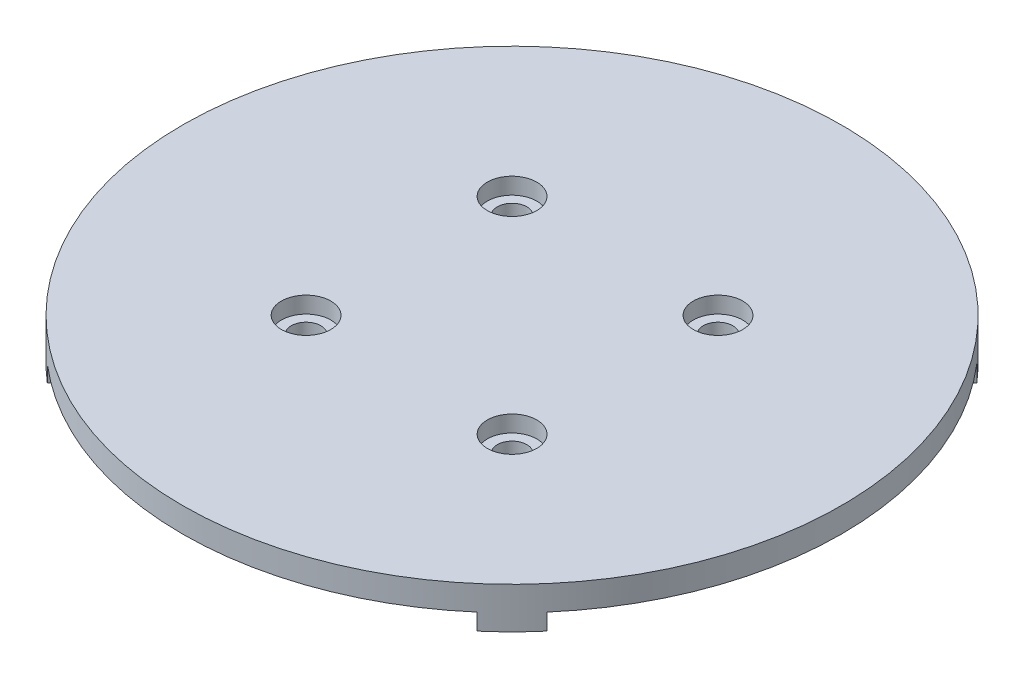
SolidWorks part; units mm, degrees
ref_plane "前视基准面" through (0, 0, 0) normal (0, 0, 1) x (1, 0, 0)
ref_plane "上视基准面" through (0, 0, 0) normal (0, 1, 0) x (1, 0, 0)
ref_plane "右视基准面" through (0, 0, 0) normal (1, 0, 0) x (0, 0, -1)
sketch "草图1" plane through (0, 0, 0) normal (0, 1, 0) x (1, 0, 0)
  circle A0 centre (0, 0) radius 40
  dimension "D1" = 80
extrude "凸台-拉伸1" add sketch "草图1" along normal blind 3 contours A0
sketch "草图2" plane through (0, 0, 0) normal (0, -1, 0) x (1, 0, 0)
  line L0 (-71.7271, 0) -> (80.6754, 0) construction
  line L1 (0, -61.079) -> (0, 71.7562) construction
  circle A0 centre (0, 0) radius 35
  circle A1 centre (0, 0) radius 30
extrude "凸台-拉伸2" add sketch "草图2" along normal blind 2
sketch "草图3" plane through (0, 0, 0) normal (0, -1, 0) x (1, 0, 0)
  circle A0 centre (0, 0) radius 15
  circle A1 centre (0, 0) radius 20
extrude "凸台-拉伸3" add sketch "草图3" along normal blind 5
sketch "草图5" plane through (0, 0, 0) normal (0, -1, 0) x (-1, 0, 0)
  line L0 (46.2077, -12.5) -> (-62.2408, -12.5) construction
  line L1 (12.5, -50.4142) -> (12.5, 52.4511) construction
  line L2 (-12.5, -45.8753) -> (-12.5, 58.6819)
  line L3 (-66.8088, 12.5) -> (53.3135, 12.5)
  line L4 (12.5, -12.5) -> (-12.5, 12.5)
  line L5 (-12.5, 12.5) -> (-12.5, -12.5)
  line L6 (-12.5, -12.5) -> (12.5, 12.5)
  circle A4 centre (12.5, -12.5) radius 1.6
  circle A5 centre (-12.5, -12.5) radius 1.6
  circle A6 centre (-12.5, 12.5) radius 1.6
  circle A7 centre (12.5, 12.5) radius 1.6
  point P8 (12.5, -12.5)
  point P9 (-12.5, -12.5)
  point P10 (12.5, 12.5)
  point P11 (-12.5, 12.5)
  point P12 (0, 0)
  dimension "D1" = 25
  dimension "D2" = 25
sketch "草图7" plane through (0, 0, 0) normal (0, -1, 0) x (1, 0, 0)
  line L0 (-26.0833, 30.3259) -> (30.3259, -26.0833)
  line L1 (26.238, -30.1922) -> (-30.1922, 26.238)
  circle A0 centre (0, 0) radius 40 construction
  circle A1 centre (0, 0) radius 40 construction
  arc A4 (-30.1922, 26.238) -> (-26.0833, 30.3259) centre (0, 0) cw
  arc A5 (30.3259, -26.0833) -> (26.238, -30.1922) centre (0, 0) cw
  dimension "D1" = 3
  dimension "D2" = 3
extrude "凸台-拉伸5" add sketch "草图7" along normal blind 2
sketch "草图6" plane through (0, 0, 0) normal (0, -1, 0) x (1, 0, 0)
  line L0 (-30.3272, -26.0819) -> (26.087, 30.3227)
  line L1 (30.3272, 26.0819) -> (-26.087, -30.3227)
  circle A0 centre (0, 0) radius 40 construction
  arc A4 (26.087, 30.3227) -> (30.3272, 26.0819) centre (0, 0) cw
  arc A5 (-30.3272, -26.0819) -> (-26.087, -30.3227) centre (0, 0) ccw
  dimension "D1" = 3
  dimension "D3" = 3
extrude "凸台-拉伸4" add sketch "草图6" along normal blind 2
sketch "草图8" plane through (0, 0, 0) normal (0, -1, 0) x (1, 0, 0)
  circle A0 centre (12.5, -12.5) radius 1.8
  circle A1 centre (12.5, 12.5) radius 1.8
  circle A2 centre (-12.5, -12.5) radius 1.8
  circle A3 centre (-12.5, 12.5) radius 1.8
extrude "切除-拉伸2" cut sketch "草图8" against normal through all both and the other way through all
sketch "草图9" plane through (0, 3, 0) normal (0, 1, 0) x (1, 0, 0)
  circle A0 centre (-12.5, 12.5) radius 3
  circle A1 centre (12.5, 12.5) radius 3
  circle A2 centre (-12.5, -12.5) radius 3
  circle A3 centre (12.5, -12.5) radius 3
extrude "切除-拉伸3" cut sketch "草图9" against normal blind 2 and the other way through all
